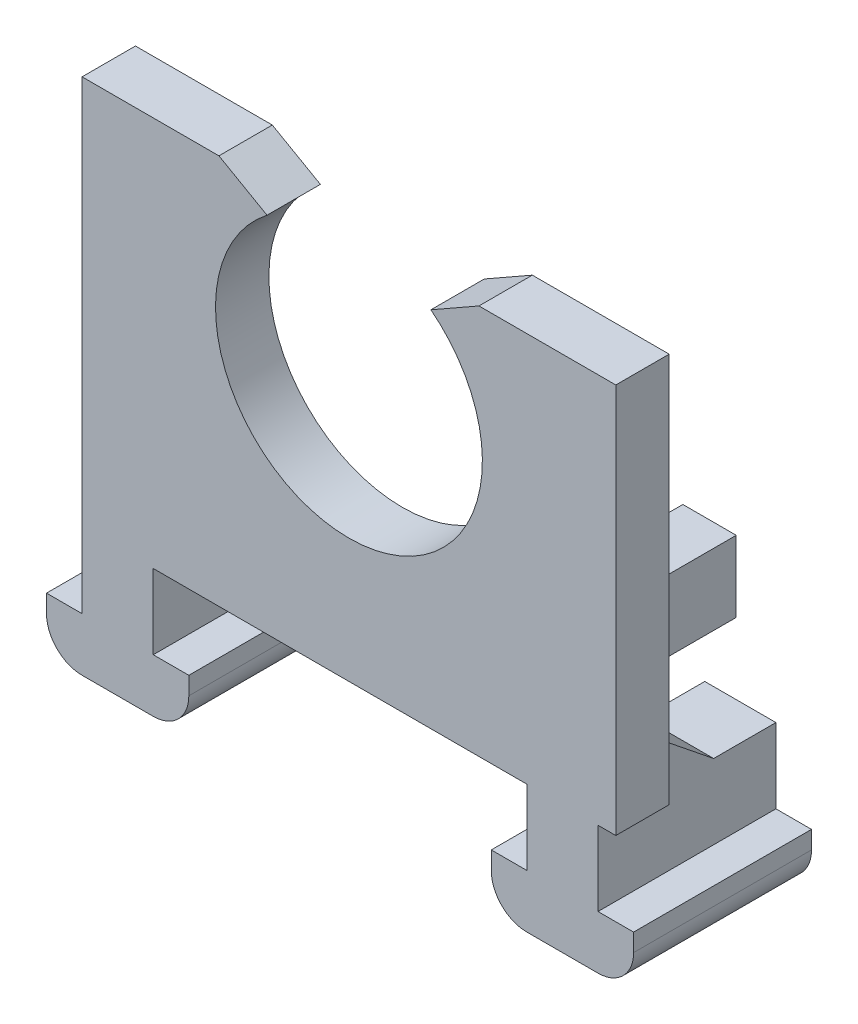
SolidWorks part; units mm, degrees
ref_plane "Спереди" through (0, 0, 0) normal (0, 0, 1) x (1, 0, 0)
ref_plane "Сверху" through (0, 0, 0) normal (0, 1, 0) x (1, 0, 0)
ref_plane "Справа" through (0, 0, 0) normal (1, 0, 0) x (0, 0, -1)
sketch "Эскиз2" plane through (0, 0, 0) normal (0, 0, 1) x (1, 0, 0)
  line L0 (-11.9857, -3.3) -> (-11.9857, -2.25)
  line L1 (18.0143, 26.7) -> (-11.9857, 26.7)
  line L2 (18.0143, 26.7) -> (18.0143, 0)
  line L4 (-11.9857, 26.7) -> (-11.9857, -3.3)
  line L5 (-11.9857, -2.25) -> (18.0143, -2.25)
  line L6 (18.0143, -2.25) -> (18.0143, 0)
  line L13 (-11.9857, 26.7) -> (-6.8352, 26.7) construction
  point P12 (30.9983, 21.5985)
  point P13 (30.9983, 4.9988)
  point P14 (30.9983, 1.9985)
  point P15 (30.9983, 24.5985)
  point P16 (32.4984, 3.4986)
  point P25 (5.1505, 21.4035)
  point P26 (5.1505, 24.4965)
  dimension "D1" = 30
  dimension "D2" = 30
extrude "Бобышка-Вытянуть1" add sketch "Эскиз2" along normal blind 2 and the other way blind 1 contours L5 L6 L2 L1 L4
sketch "Sketch1" plane through (0, 0, 2) normal (0, 0, 1) x (1, 0, 0)
  line L0 (-7.9857, -6.45) -> (-5.9857, -6.45)
  line L1 (-11.9857, -2.25) -> (-7.9857, -2.25)
  line L2 (-11.9857, -2.25) -> (-11.9857, -6.45)
  line L3 (-11.9857, -6.45) -> (-7.9857, -6.45)
  line L4 (-7.9857, -2.25) -> (-7.9857, -6.45)
  line L5 (-5.9857, -6.45) -> (-5.9857, -7.45)
  line L6 (-7.9857, -9.45) -> (-11.9857, -9.45)
  line L7 (-9.9857, -2.25) -> (-9.9857, -9.45) construction
  line L8 (-11.9857, -6.45) -> (-13.9857, -6.45)
  line L9 (-13.9857, -6.45) -> (-13.9857, -7.45)
  arc A0 (-5.9857, -7.45) -> (-7.9857, -9.45) centre (-7.9857, -7.45) cw
  arc A1 (-13.9857, -7.45) -> (-11.9857, -9.45) centre (-11.9857, -7.45) ccw
  point P11 (-5.9857, -9.45)
  dimension "D5" = 2
  dimension "D1" = 4
  dimension "D2" = 4.2
  dimension "D3" = 3
  dimension "D4" = 4
extrude "Boss-Extrude1" add sketch "Sketch1" against normal blind 10
pattern_linear "LPattern1" count 2 spacing 25 along (1, 0, 0) of "Boss-Extrude1"
sketch "Sketch2" plane through (0, 0, 2) normal (0, 0, -1) x (-1, 0, 0)
  line L1 (-10.7836, -2.25) -> (-7.7836, -2.25)
  line L2 (-10.7836, -2.25) -> (-10.7836, 1.75)
  line L3 (-10.7836, 1.75) -> (-7.7836, 1.75)
  line L4 (-7.7836, -2.25) -> (-7.7836, 1.75)
  dimension "D1" = 4
  dimension "D2" = 3
extrude "Boss-Extrude2" add sketch "Sketch2" along normal blind 14 contours L2 L3 L4 L1
sketch "Sketch3" plane through (13.0143, 0, 0) normal (-1, 0, 0) x (0, 0, 1)
  line L0 (-4.5, -2.25) -> (-1, -2.25)
  line L1 (-8, -2.25) -> (-1, -2.25) construction
  line L2 (-1, -2.25) -> (-1, 0.5589)
  line L3 (-1, 0.5589) -> (-4.5, -2.25)
extrude "Boss-Extrude3" add sketch "Sketch3" against normal blind 4
pattern_linear "LPattern2" count 2 spacing 25 along (-1, 0, 0) of "Boss-Extrude3"
sketch "Sketch4" plane through (0, 0, -1) normal (0, 0, -1) x (-1, 0, 0)
  line L0 (-3.0143, 26.7) -> (-3.0143, -2.25) construction
  line L1 (-18.0143, 26.7) -> (11.9857, 26.7) construction
  line L2 (7.9857, -2.25) -> (-7.7836, -2.25) construction
  line L4 (-10.3213, 19.6829) -> (-7.6197, 18.1445)
  line L6 (-10.3213, 19.6829) -> (-18.0143, 19.6829)
  line L7 (4.2927, 19.6829) -> (1.5911, 18.1445)
  line L8 (-18.0143, -2.25) -> (-18.0143, 26.7) construction
  line L9 (-18.0143, 19.6829) -> (-22.588, 29.7401)
  line L10 (-22.588, 29.7401) -> (19.5609, 30.4232)
  line L11 (19.5609, 30.4232) -> (13.3853, 19.6829)
  line L12 (13.3853, 19.6829) -> (4.2927, 19.6829)
  arc A0 (-10.5143, 12.225) -> (4.4857, 12.225) centre (-3.0143, 12.225) ccw
  arc A1 (-10.5143, 12.225) -> (-7.6197, 18.1445) centre (-3.0143, 12.225) cw
  arc A2 (4.4857, 12.225) -> (1.5911, 18.1445) centre (-3.0143, 12.225) ccw
  dimension "D1" = 15
extrude "Cut-Extrude1" cut sketch "Sketch4" against normal blind 10
